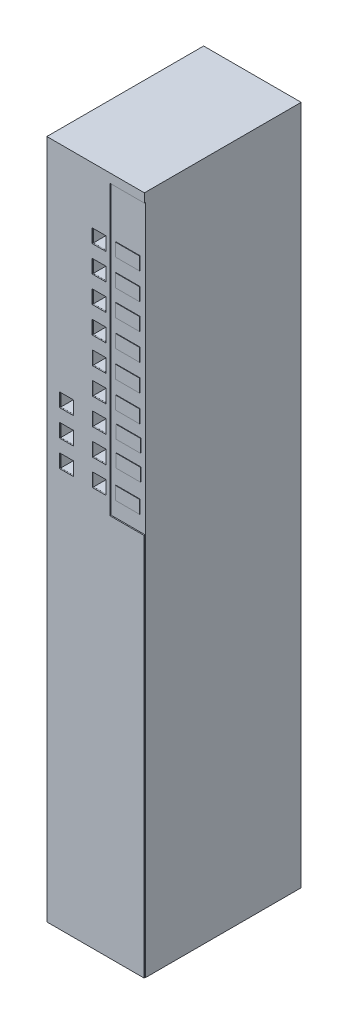
SolidWorks part; units mm, degrees
ref_plane "Alzado" through (0, 0, 0) normal (0, 0, 1) x (1, 0, 0)
ref_plane "Planta" through (0, 0, 0) normal (0, 1, 0) x (1, 0, 0)
ref_plane "Vista lateral" through (0, 0, 0) normal (1, 0, 0) x (0, 0, -1)
sketch "Croquis1" plane through (0, 0, 0) normal (0, 0, 1) x (1, 0, 0)
  line L5 (162.4902, -151.4578) -> (187.4902, -151.4578)
  line L6 (102.9371, 138.5272) -> (127.9371, 138.5272)
  line L7 (102.9371, 138.5272) -> (102.9371, 113.5272)
  line L8 (127.9371, 138.5272) -> (127.9371, 113.5272)
  line L9 (102.9371, 113.5272) -> (127.9371, 113.5272)
  line L10 (102.9371, 90.1942) -> (127.9371, 90.1942)
  line L11 (102.9371, 90.1942) -> (102.9371, 65.1942)
  line L12 (127.9371, 90.1942) -> (127.9371, 65.1942)
  line L13 (102.9371, 65.1942) -> (127.9371, 65.1942)
  line L14 (102.9371, 41.8642) -> (127.9371, 41.8642)
  line L15 (102.9371, 41.8642) -> (102.9371, 16.8642)
  line L16 (127.9371, 41.8642) -> (127.9371, 16.8642)
  line L17 (102.9371, 16.8642) -> (127.9371, 16.8642)
  line L18 (102.9371, -6.4658) -> (127.9371, -6.4658)
  line L19 (102.9371, -6.4658) -> (102.9371, -31.4658)
  line L20 (127.9371, -6.4658) -> (127.9371, -31.4658)
  line L21 (102.9371, -31.4658) -> (127.9371, -31.4658)
  line L22 (127.4902, -79.7915) -> (102.4902, -79.7915)
  line L23 (127.4902, -79.7915) -> (127.4902, -54.7915)
  line L24 (102.4902, -79.7915) -> (102.4902, -54.7915)
  line L25 (127.4902, -54.7915) -> (102.4902, -54.7915)
  line L26 (102.4902, -103.1248) -> (127.4902, -103.1248)
  line L27 (102.4902, -103.1248) -> (102.4902, -128.1248)
  line L28 (127.4902, -103.1248) -> (127.4902, -128.1248)
  line L29 (102.4902, -128.1248) -> (127.4902, -128.1248)
  line L30 (102.4902, -151.4578) -> (127.4902, -151.4578)
  line L31 (102.4902, -151.4578) -> (102.4902, -176.4578)
  line L32 (127.4902, -151.4578) -> (127.4902, -176.4578)
  line L33 (102.4902, -176.4578) -> (127.4902, -176.4578)
  line L34 (102.4902, -199.7878) -> (127.4902, -199.7878)
  line L35 (102.4902, -199.7878) -> (102.4902, -224.7878)
  line L36 (127.4902, -199.7878) -> (127.4902, -224.7878)
  line L37 (102.4902, -224.7878) -> (127.4902, -224.7878)
  line L38 (102.4902, -248.1178) -> (127.4902, -248.1178)
  line L39 (102.4902, -248.1178) -> (102.4902, -273.1178)
  line L40 (127.4902, -248.1178) -> (127.4902, -273.1178)
  line L41 (102.4902, -273.1178) -> (127.4902, -273.1178)
  line L42 (162.4902, -151.4578) -> (162.4902, -176.4578)
  line L43 (187.4902, -151.4578) -> (187.4902, -176.4578)
  line L44 (162.4902, -176.4578) -> (187.4902, -176.4578)
  line L45 (32.4902, -1003.7495) -> (211.0781, -1003.7495)
  line L46 (32.4902, -1003.7495) -> (32.4902, 241.6983)
  line L47 (162.4902, -199.7878) -> (187.4902, -199.7878)
  line L48 (162.4902, -199.7878) -> (162.4902, -224.7878)
  line L49 (187.4902, -199.7878) -> (187.4902, -224.7878)
  line L50 (162.4902, -224.7878) -> (187.4902, -224.7878)
  line L51 (162.4902, -248.1178) -> (187.4902, -248.1178)
  line L52 (162.4902, -248.1178) -> (162.4902, -273.1178)
  line L53 (187.4902, -248.1178) -> (187.4902, -273.1178)
  line L54 (162.4902, -273.1178) -> (187.4902, -273.1178)
  line L55 (211.0781, -1003.7495) -> (211.0781, 241.6983)
  line L56 (32.4902, 241.6983) -> (211.0781, 241.6983)
  point P2 (102.9371, 138.5272)
  point P7 (102.9371, 90.1942)
  point P10 (102.9371, 41.8642)
  point P15 (102.9371, -6.4658)
  point P25 (102.4902, -103.1248)
  point P31 (102.4902, -151.4578)
  point P34 (102.4902, -199.7878)
  point P39 (102.4902, -248.1178)
  point P62 (32.4902, -273.1178)
  dimension "D3" = 25
  dimension "D4" = 23.333
  dimension "D5" = 25
  dimension "D7" = 23.33
  dimension "D8" = 25
  dimension "D9" = 23.33
  dimension "D10" = 25
  dimension "D11" = 23.3333
  dimension "D12" = 25
  dimension "D13" = 23.333
  dimension "D14" = 25
  dimension "D15" = 25
  dimension "D16" = 23.33
  dimension "D17" = 25
  dimension "D18" = 23.33
extrude "Saliente-Extruir2" add sketch "Croquis1" against normal blind 285
ref_plane "Plano1" through (0, 0, -285) normal (0, 0, -1) x (-1, 0, 0)
sketch "Croquis2" plane through (0, 0, -285) normal (0, 0, -1) x (-1, 0, 0)
  line L0 (-211.0781, 241.6983) -> (-32.4902, 241.6983)
  line L1 (-211.0781, 241.6983) -> (-211.0781, -311.1466)
  line L2 (-32.4902, 241.6983) -> (-32.4902, -311.1466)
  line L3 (-211.0781, -311.1466) -> (-32.4902, -311.1466)
extrude "Saliente-Extruir3" add sketch "Croquis2" against normal blind 1
ref_plane "Plano4" through (0, 0, 2) normal (0, 0, 1) x (1, 0, 0)
sketch "Croquis5" plane through (0, 0, 0) normal (0, 0, 1) x (1, 0, 0)
  line L4 (162.7769, -151.5671) -> (187.7769, -151.5671)
  line L5 (103.2238, 138.4179) -> (128.2238, 138.4179)
  line L6 (103.2238, 138.4179) -> (103.2238, 113.4179)
  line L7 (128.2238, 138.4179) -> (128.2238, 113.4179)
  line L8 (103.2238, 113.4179) -> (128.2238, 113.4179)
  line L9 (103.2238, 90.0849) -> (128.2238, 90.0849)
  line L10 (103.2238, 90.0849) -> (103.2238, 65.0849)
  line L11 (128.2238, 90.0849) -> (128.2238, 65.0849)
  line L12 (103.2238, 65.0849) -> (128.2238, 65.0849)
  line L13 (103.2238, 41.7549) -> (128.2238, 41.7549)
  line L14 (103.2238, 41.7549) -> (103.2238, 16.7549)
  line L15 (128.2238, 41.7549) -> (128.2238, 16.7549)
  line L16 (103.2238, 16.7549) -> (128.2238, 16.7549)
  line L17 (103.2238, -6.5751) -> (128.2238, -6.5751)
  line L18 (103.2238, -6.5751) -> (103.2238, -31.5751)
  line L19 (128.2238, -6.5751) -> (128.2238, -31.5751)
  line L20 (103.2238, -31.5751) -> (128.2238, -31.5751)
  line L21 (127.7769, -79.9008) -> (102.7769, -79.9008)
  line L22 (127.7769, -79.9008) -> (127.7769, -54.9008)
  line L23 (102.7769, -79.9008) -> (102.7769, -54.9008)
  line L24 (127.7769, -54.9008) -> (102.7769, -54.9008)
  line L25 (102.7769, -103.2341) -> (127.7769, -103.2341)
  line L26 (102.7769, -103.2341) -> (102.7769, -128.2341)
  line L27 (127.7769, -103.2341) -> (127.7769, -128.2341)
  line L28 (102.7769, -128.2341) -> (127.7769, -128.2341)
  line L29 (102.7769, -151.5671) -> (127.7769, -151.5671)
  line L30 (102.7769, -151.5671) -> (102.7769, -176.5671)
  line L31 (127.7769, -151.5671) -> (127.7769, -176.5671)
  line L32 (102.7769, -176.5671) -> (127.7769, -176.5671)
  line L33 (102.7769, -199.8971) -> (127.7769, -199.8971)
  line L34 (102.7769, -199.8971) -> (102.7769, -224.8971)
  line L35 (127.7769, -199.8971) -> (127.7769, -224.8971)
  line L36 (102.7769, -224.8971) -> (127.7769, -224.8971)
  line L37 (102.7769, -248.2271) -> (127.7769, -248.2271)
  line L38 (102.7769, -248.2271) -> (102.7769, -273.2271)
  line L39 (127.7769, -248.2271) -> (127.7769, -273.2271)
  line L40 (102.7769, -273.2271) -> (127.7769, -273.2271)
  line L41 (162.7769, -151.5671) -> (162.7769, -176.5671)
  line L42 (187.7769, -151.5671) -> (187.7769, -176.5671)
  line L43 (162.7769, -176.5671) -> (187.7769, -176.5671)
  line L44 (40.1339, 241.6983) -> (187.7769, 241.6983)
  line L45 (95.7914, -301.9028) -> (33.3785, -301.9028)
  line L46 (162.7769, -199.8971) -> (187.7769, -199.8971)
  line L47 (162.7769, -199.8971) -> (162.7769, -224.8971)
  line L48 (187.7769, -199.8971) -> (187.7769, -224.8971)
  line L49 (162.7769, -224.8971) -> (187.7769, -224.8971)
  line L50 (162.7769, -248.2271) -> (187.7769, -248.2271)
  line L51 (162.7769, -248.2271) -> (162.7769, -273.2271)
  line L52 (187.7769, -248.2271) -> (187.7769, -273.2271)
  line L53 (162.7769, -273.2271) -> (187.7769, -273.2271)
  line L54 (211.0781, 241.6983) -> (32.4902, 241.6983) construction
  line L55 (32.4902, -1003.7495) -> (211.0781, -1003.7495) construction
  line L56 (95.7914, 225.3423) -> (32.4902, 225.3423)
  line L57 (32.4902, 241.6983) -> (32.4902, -1003.7495) construction
  line L58 (95.7914, 225.3423) -> (95.7914, -301.9028)
  line L59 (32.4902, 225.3423) -> (32.4902, 241.6983)
  line L60 (32.4902, 241.6983) -> (40.1339, 241.6983)
  line L61 (33.3785, -301.9028) -> (33.3785, -1003.7495)
  line L62 (211.1346, -1003.7495) -> (211.1346, 241.6983)
  line L63 (211.1346, 241.6983) -> (187.7769, 241.6983)
  line L64 (33.3785, -1003.7495) -> (211.1346, -1003.7495)
  point P1 (103.2238, 138.4179)
  point P6 (103.2238, 90.0849)
  point P9 (103.2238, 41.7549)
  point P14 (103.2238, -6.5751)
  point P24 (102.7769, -103.2341)
  point P30 (102.7769, -151.5671)
  point P33 (102.7769, -199.8971)
  point P38 (102.7769, -248.2271)
  dimension "D2" = 25
  dimension "D3" = 23.333
  dimension "D4" = 25
  dimension "D6" = 23.3333
  dimension "D7" = 25
  dimension "D8" = 23.333
  dimension "D9" = 25
  dimension "D10" = 25
extrude "Saliente-Extruir4" add sketch "Croquis5" along normal blind 2
ref_plane "Plano5" through (0, 0, 0) normal (0, 0, 1) x (1, 0, 0)
sketch "Croquis10" plane through (0, 0, 0) normal (0, 0, 1) x (1, 0, 0)
  line L4 (86.6248, 87.214) -> (42.2297, 87.214)
  line L5 (86.6248, 87.214) -> (86.6248, 63.5596)
  line L6 (42.2297, 87.214) -> (42.2297, 63.5596)
  line L7 (86.6248, 63.5596) -> (42.2297, 63.5596)
  line L8 (86.6248, -8.8817) -> (42.2297, -8.8817)
  line L9 (86.6248, -8.8817) -> (86.6248, -32.5361)
  line L10 (42.2297, -8.8817) -> (42.2297, -32.5361)
  line L11 (86.6248, -32.5361) -> (42.2297, -32.5361)
  line L12 (86.6248, -57.6688) -> (42.2297, -57.6688)
  line L13 (86.6248, -57.6688) -> (86.6248, -81.3231)
  line L14 (42.2297, -57.6688) -> (42.2297, -81.3231)
  line L15 (86.6248, -81.3231) -> (42.2297, -81.3231)
  line L16 (86.6248, -106.4558) -> (42.2297, -106.4558)
  line L17 (86.6248, -106.4558) -> (86.6248, -130.1101)
  line L18 (42.2297, -106.4558) -> (42.2297, -130.1101)
  line L19 (86.6248, -130.1101) -> (42.2297, -130.1101)
  line L20 (85.1464, -152.2861) -> (40.7513, -152.2861)
  line L21 (85.1464, -152.2861) -> (85.1464, -175.9404)
  line L22 (40.7513, -152.2861) -> (40.7513, -175.9404)
  line L23 (85.1464, -175.9404) -> (40.7513, -175.9404)
  line L24 (85.1464, -198.1163) -> (40.7513, -198.1163)
  line L25 (85.1464, -198.1163) -> (85.1464, -221.7706)
  line L26 (40.7513, -198.1163) -> (40.7513, -221.7706)
  line L27 (85.1464, -221.7706) -> (40.7513, -221.7706)
  line L28 (86.6248, 39.9053) -> (42.2297, 39.9053)
  line L29 (86.6248, 39.9053) -> (86.6248, 16.251)
  line L30 (42.2297, 39.9053) -> (42.2297, 16.251)
  line L31 (86.6248, 16.251) -> (42.2297, 16.251)
  line L32 (86.6248, 136.001) -> (42.2297, 136.001)
  line L33 (86.6248, 136.001) -> (86.6248, 112.3467)
  line L34 (42.2297, 136.001) -> (42.2297, 112.3467)
  line L35 (86.6248, 112.3467) -> (42.2297, 112.3467)
  line L37 (86.6248, -249.8602) -> (42.2297, -249.8602)
  line L38 (86.6248, -249.8602) -> (86.6248, -273.5145)
  line L39 (42.2297, -249.8602) -> (42.2297, -273.5145)
  line L40 (86.6248, -273.5145) -> (42.2297, -273.5145)
extrude "Saliente-Extruir5" add sketch "Croquis10" along normal blind 1
ref_plane "Plano6" through (311.0781, 0, 0) normal (1, 0, 0) x (0, 0, -1)
mirror "Simetría1" about plane through (311.0781, 0, 0) normal (1, 0, 0) of bodies 114
delete or keep bodies "Sólido-Eliminar1" type delete bodies bodies 114
